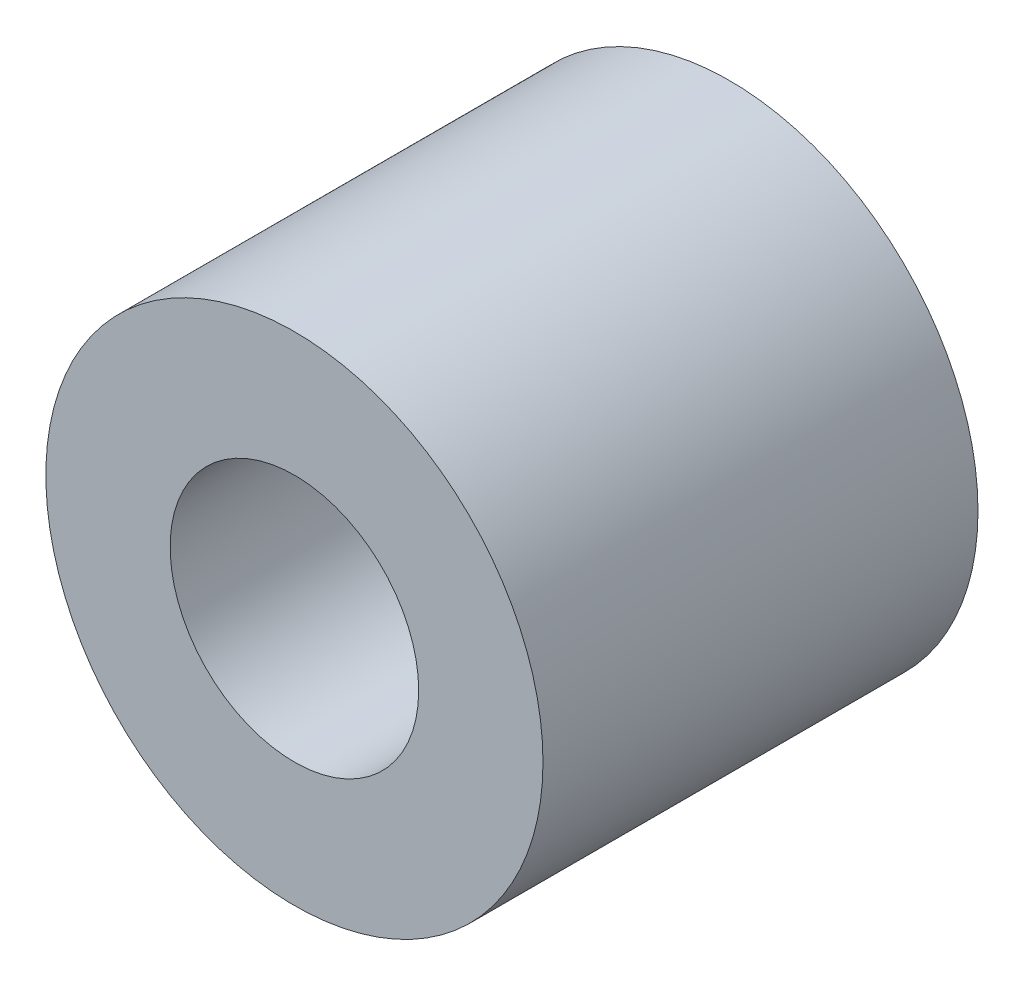
SolidWorks part; units mm, degrees
material "6061-T6 (SS)"
ref_plane "Front Plane" through (0, 0, 0) normal (0, 0, 1) x (1, 0, 0)
ref_plane "Top Plane" through (0, 0, 0) normal (0, 1, 0) x (1, 0, 0)
ref_plane "Right Plane" through (0, 0, 0) normal (1, 0, 0) x (0, 0, -1)
sketch "Sketch1" plane through (0, 0, 0) normal (0, 0, 1) x (1, 0, 0)
  circle A0 centre (0, 0) radius 3.175
  circle A1 centre (0, 0) radius 6.35
  dimension "D1" = 12.7
  dimension "D2" = 6.35
extrude "Boss-Extrude1" add sketch "Sketch1" against normal blind 11.1125
